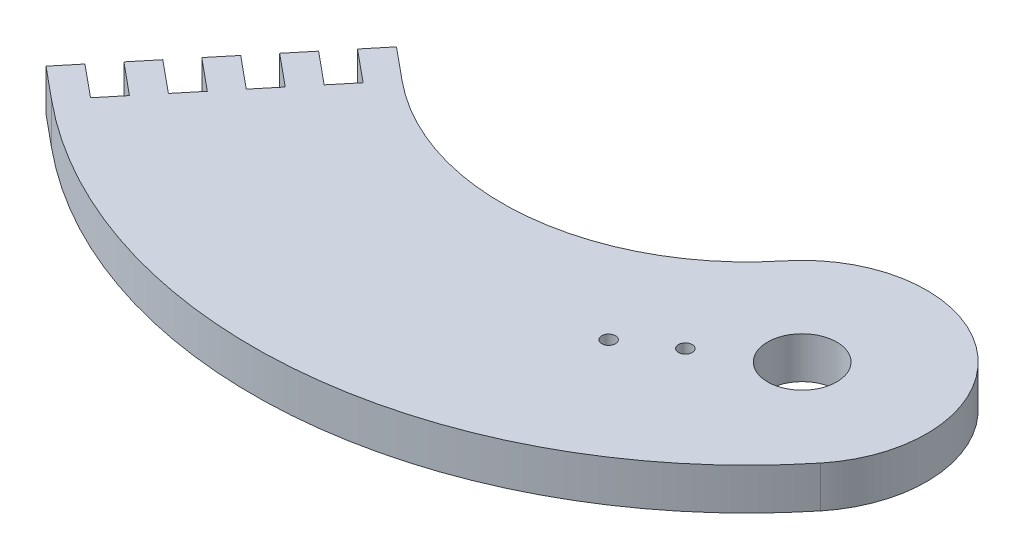
SolidWorks part; units mm, degrees
ref_plane "Front Plane" through (0, 0, 0) normal (0, 0, 1) x (1, 0, 0)
ref_plane "Top Plane" through (0, 0, 0) normal (0, 1, 0) x (1, 0, 0)
ref_plane "Right Plane" through (0, 0, 0) normal (1, 0, 0) x (0, 0, -1)
sketch "Sketch1" plane through (0, 0, 0) normal (0, 1, 0) x (1, 0, 0)
  line L0 (-33.3586, 1.613) -> (-34.6321, 0.0708)
  line L1 (-35.6718, 3.5232) -> (-33.3586, 1.613)
  line L2 (-34.3983, 5.0654) -> (-35.6718, 3.5232)
  line L3 (-36.9453, 1.9811) -> (-34.6321, 0.0708)
  line L4 (-34.3983, 5.0654) -> (-32.0851, 3.1551)
  line L5 (-38.2188, 0.4389) -> (-35.9056, -1.4713)
  line L6 (-39.4923, -1.1032) -> (-37.1791, -3.0135)
  line L7 (-40.7658, -2.6453) -> (-38.4526, -4.5556)
  line L8 (-42.0393, -4.1875) -> (-39.7261, -6.0977)
  line L9 (-43.3128, -5.7296) -> (-40.9996, -7.6399)
  line L10 (-44.5863, -7.2718) -> (-42.2731, -9.182)
  line L11 (-45.8598, -8.8139) -> (-43.5466, -10.7241)
  line L12 (-36.9453, 1.9811) -> (-38.2188, 0.4389)
  line L13 (-39.4923, -1.1032) -> (-40.7658, -2.6453)
  line L14 (-42.0393, -4.1875) -> (-43.3128, -5.7296)
  line L15 (-44.5863, -7.2718) -> (-45.8598, -8.8139)
  line L16 (-40.9996, -7.6399) -> (-42.2731, -9.182)
  line L17 (-38.4526, -4.5556) -> (-39.7261, -6.0977)
  line L18 (-35.9056, -1.4713) -> (-37.1791, -3.0135)
  line L19 (-32.0851, 3.1551) -> (-32.0851, -15.1603) construction
  line L20 (0, 0) -> (-9.7217, 0) construction
  line L21 (0, 0) -> (-14.1902, -9.478) construction
  circle A0 centre (0, 0) radius 2.5
  arc A1 (6.9923, -5.6663) -> (-6.9923, 5.6663) centre (0, 0) ccw
  arc A2 (-32.0851, 3.1551) -> (-6.9923, 5.6663) centre (-20.7828, 16.8416) ccw
  arc A3 (-43.5466, -10.7241) -> (6.9923, -5.6663) centre (-20.7828, 16.8416) ccw
  circle A4 centre (-5.0642, -3.3825) radius 0.5
  circle A5 centre (-8.3905, -5.6042) radius 0.5
  dimension "D4" = 5
  dimension "D5" = 18
  dimension "D7" = 17.75
  dimension "D8" = 90.53
  dimension "D10" = 1
  dimension "D2" = 3
  dimension "D3" = 2
  dimension "D6" = 39.55
  dimension "D9" = 33.74
  dimension "D11" = 6.09
  dimension "D12" = 4
  dimension "D1" = 10
extrude "Boss-Extrude1" add sketch "Sketch1" along normal blind 3
